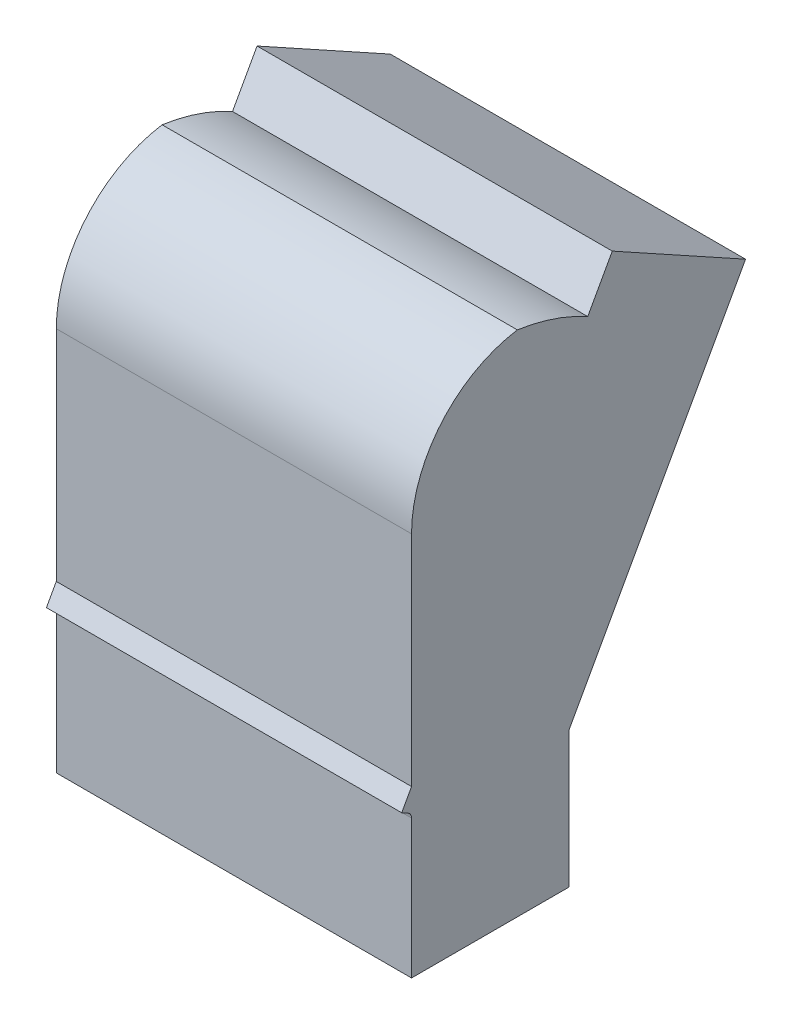
SolidWorks part; units mm, degrees
material "6061-T6 (SS)"
ref_plane "Front Plane" through (0, 0, 0) normal (0, 0, 1) x (1, 0, 0)
ref_plane "Top Plane" through (0, 0, 0) normal (0, 1, 0) x (1, 0, 0)
ref_plane "Right Plane" through (0, 0, 0) normal (1, 0, 0) x (0, 0, -1)
sketch "Sketch1" plane through (0, 0, 0) normal (1, 0, 0) x (0, 0, -1)
  line L0 (0, 0) -> (-78.74, 0)
  line L1 (-78.74, 0) -> (-78.74, 69.342)
  line L2 (0, 0) -> (0, 67.056)
  line L3 (3.429, 70.485) -> (54.229, 70.485)
  line L4 (-82.169, 72.771) -> (-124.044, 72.771)
  line L5 (54.229, 70.485) -> (54.229, 166.0906)
  arc A0 (0, 67.056) -> (3.429, 70.485) centre (3.429, 67.056) cw
  arc A1 (-78.74, 69.342) -> (-82.169, 72.771) centre (-82.169, 69.342) ccw
  point P9 (0, 70.485)
  point P12 (-78.74, 72.771)
  dimension "D5" = 3.429
  dimension "D1" = 78.74
  dimension "D2" = 72.771
  dimension "D3" = 2.286
  dimension "D4" = 54.229
  dimension "D6" = 95.6056
sketch "Sketch2" plane through (0, 0, 0) normal (1, 0, 0) x (0, 0, -1)
  line L0 (-78.74, 69.342) -> (-5.4785, 48.385) construction
  line L1 (-78.74, 69.342) -> (-25.7886, 254.4493) construction
  line L2 (-5.4785, 48.385) -> (47.4729, 233.4923) construction
  line L3 (-25.7886, 254.4493) -> (47.4729, 233.4923) construction
  line L4 (-78.74, 0) -> (-78.74, 69.342) construction
  line L5 (-78.74, 34.671) -> (-2.7371, 29.1945) construction
  line L6 (-78.74, 34.671) -> (-64.9027, 226.7051) construction
  line L7 (-2.7371, 29.1945) -> (11.1002, 221.2286) construction
  line L8 (-64.9027, 226.7051) -> (11.1002, 221.2286) construction
  line L9 (-78.74, 2.946) -> (-2.597, 0) construction
  line L10 (-78.74, 2.946) -> (-71.2965, 195.334) construction
  line L11 (-2.597, 0) -> (4.8465, 192.3881) construction
  line L12 (-71.2965, 195.334) -> (4.8465, 192.3881) construction
  line L13 (0, 0) -> (-78.74, 0) construction
  line L14 (-78.74, 0) -> (-78.74, 71.365) construction
  line L15 (-83.6624, 74.0847) -> (-16.9655, 37.234) construction
  line L16 (-83.6624, 74.0847) -> (9.447, 242.6054) construction
  line L17 (-16.9655, 37.234) -> (76.1438, 205.7547) construction
  line L18 (9.447, 242.6054) -> (76.1438, 205.7547) construction
  line L19 (9.447, 242.6054) -> (76.1438, 205.7547)
  line L20 (76.1438, 205.7547) -> (0.4276, 68.7143)
  line L21 (0, 67.056) -> (0, 0)
  line L22 (0, 0) -> (-78.74, 0)
  line L23 (-78.74, 82.9938) -> (-83.6624, 74.0847)
  line L24 (-83.6624, 74.0847) -> (-78.74, 71.365) construction
  line L25 (-78.74, 82.9938) -> (-78.74, 192.532)
  line L26 (-83.6624, 74.0847) -> (-80.5107, 72.3434)
  line L27 (-78.74, 69.342) -> (-78.74, 0)
  arc A0 (3.429, 70.485) -> (0, 67.056) centre (3.429, 67.056) ccw construction
  arc A1 (-78.74, 192.532) -> (-25.7886, 254.4493) centre (-16.0636, 192.532) cw
  arc A2 (-78.74, 69.342) -> (-82.169, 72.771) centre (-82.169, 69.342) ccw construction
  arc A3 (-25.7886, 254.4493) -> (9.447, 242.6054) centre (-40.6231, 151.9825) cw
  arc A4 (-80.5107, 72.3434) -> (-78.74, 69.342) centre (-82.169, 69.342) cw
  arc A5 (0, 67.056) -> (0.4276, 68.7143) centre (3.429, 67.056) cw
  dimension "D1" = 76.2
  dimension "D2" = 192.532
  dimension "D3" = 192.532
extrude "Boss-Extrude1" add sketch "Sketch2" along normal blind 177.8
sketch "Sketch3" plane through (177.8, 0, 0) normal (1, 0, 0) x (0, 0, -1)
  line L0 (76.1438, 205.7547) -> (88.4274, 227.987)
  line L1 (88.4274, 227.987) -> (21.7305, 264.8376)
  line L2 (21.7305, 264.8376) -> (9.447, 242.6054)
  line L3 (76.1438, 205.7547) -> (9.447, 242.6054) construction
  line L4 (9.447, 242.6054) -> (76.1438, 205.7547)
  dimension "D1" = 25.4
extrude "Boss-Extrude2" add sketch "Sketch3" against normal up to surface (177.8 mm away) up to face at (0, 111.793, 35.7913)
